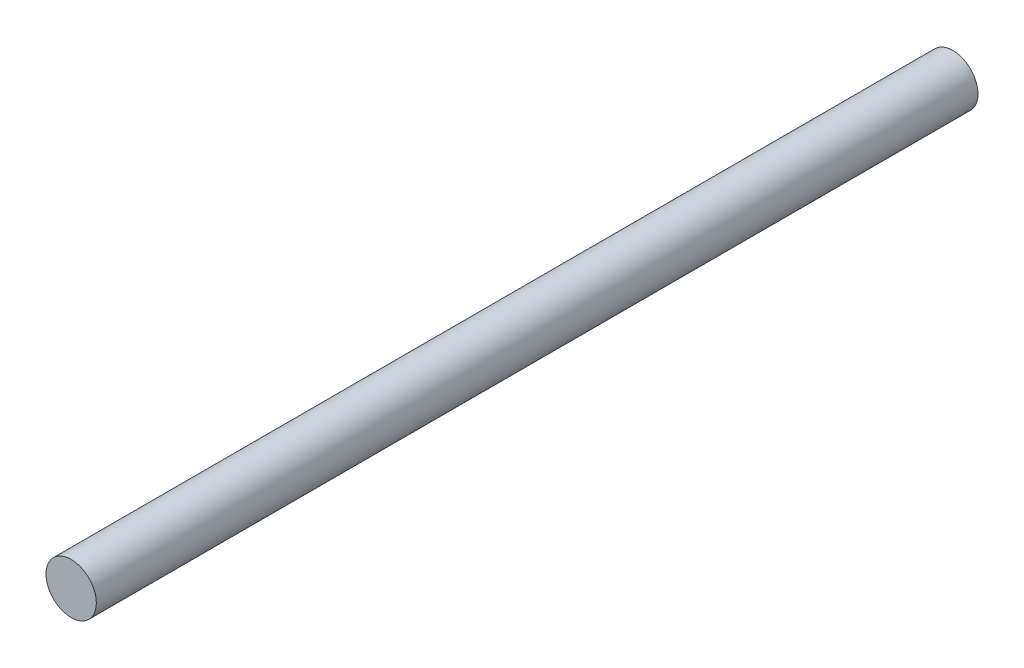
SolidWorks part; units mm, degrees
ref_plane "Plano frontal" through (0, 0, 0) normal (0, 0, 1) x (1, 0, 0)
ref_plane "Plano superior" through (0, 0, 0) normal (0, 1, 0) x (1, 0, 0)
ref_plane "Plano direito" through (0, 0, 0) normal (1, 0, 0) x (0, 0, -1)
sketch "Esboço1" plane through (0, 0, 0) normal (0, 0, 1) x (1, 0, 0)
  circle A0 centre (0, 0) radius 4
  dimension "D1" = 8
extrude "Ressalto-extrusão1" add sketch "Esboço1" along normal blind 140
